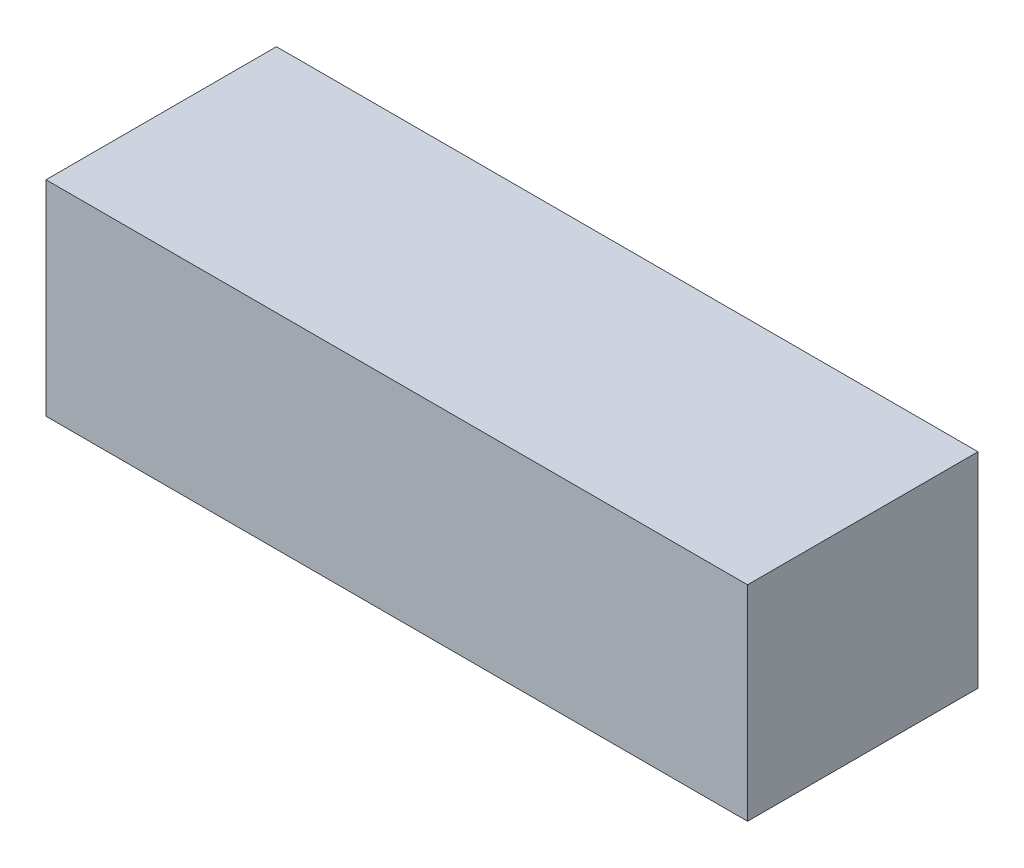
SolidWorks part; units mm, degrees
ref_plane "Front Plane" through (0, 0, 0) normal (0, 0, 1) x (1, 0, 0)
ref_plane "Top Plane" through (0, 0, 0) normal (0, 1, 0) x (1, 0, 0)
ref_plane "Right Plane" through (0, 0, 0) normal (1, 0, 0) x (0, 0, -1)
sketch "Sketch1" plane through (0, 0, 0) normal (0, 0, 1) x (1, 0, 0)
  line L1 (-62.2831, 17.8257) -> (74.7169, 17.8257)
  line L2 (-62.2831, 17.8257) -> (-62.2831, -22.1743)
  line L3 (-62.2831, -22.1743) -> (74.7169, -22.1743)
  line L4 (74.7169, 17.8257) -> (74.7169, -22.1743)
  dimension "D1" = 137
  dimension "D2" = 40
extrude "Boss-Extrude1" add sketch "Sketch1" along normal mid plane 45
